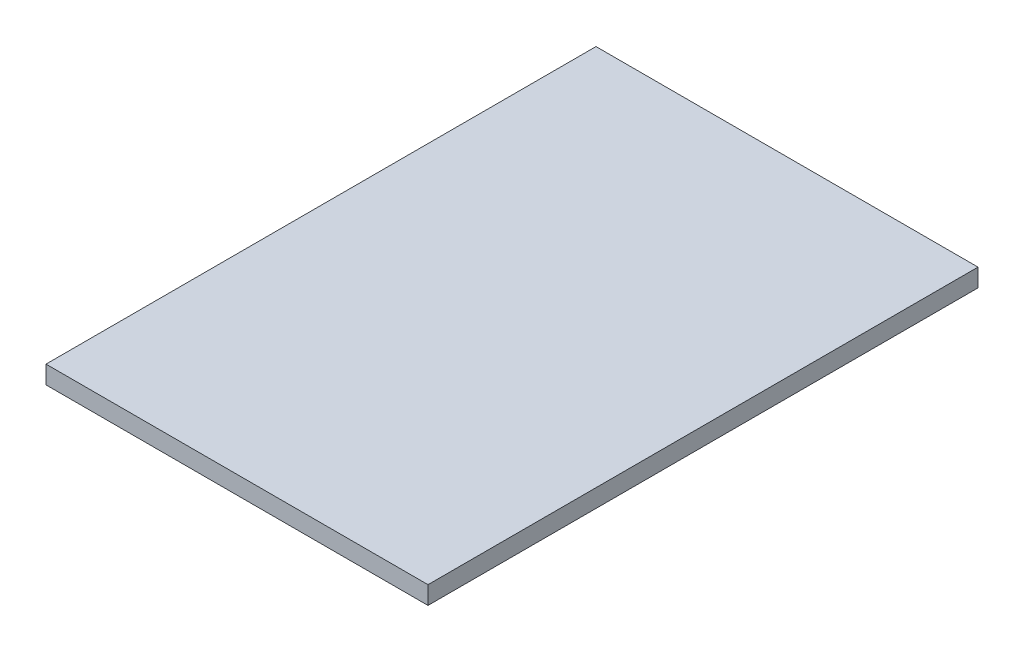
SolidWorks part; units mm, degrees
ref_plane "Front Plane" through (0, 0, 0) normal (0, 0, 1) x (1, 0, 0)
ref_plane "Top Plane" through (0, 0, 0) normal (0, 1, 0) x (1, 0, 0)
ref_plane "Right Plane" through (0, 0, 0) normal (1, 0, 0) x (0, 0, -1)
sketch "Sketch1" plane through (0, 0, 0) normal (0, 1, 0) x (1, 0, 0)
  line L1 (-191, 275) -> (191, 275)
  line L2 (-191, 275) -> (-191, -275)
  line L3 (-191, -275) -> (191, -275)
  line L4 (191, 275) -> (191, -275)
  line L5 (-191, 275) -> (191, -275) construction
  line L6 (-191, -275) -> (191, 275) construction
  point P0 (0, 0)
  dimension "D1" = 382
  dimension "D2" = 550
extrude "Boss-Extrude1" add sketch "Sketch1" along normal blind 18
